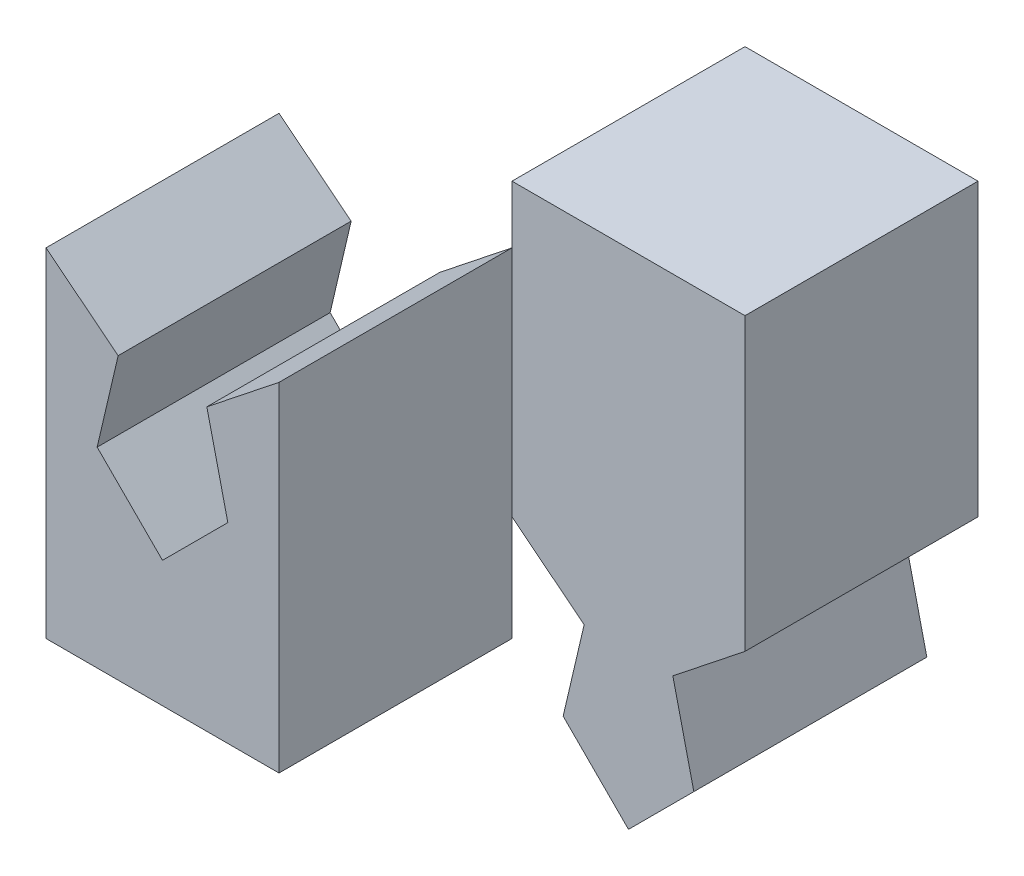
SolidWorks part; units mm, degrees
ref_plane "Front Plane" through (0, 0, 0) normal (0, 0, 1) x (1, 0, 0)
ref_plane "Top Plane" through (0, 0, 0) normal (0, 1, 0) x (1, 0, 0)
ref_plane "Right Plane" through (0, 0, 0) normal (1, 0, 0) x (0, 0, -1)
sketch "Sketch2" plane through (0, 0, 0) normal (0, 1, 0) x (1, 0, 0)
  line L1 (-2.5, 2.5) -> (2.5, 2.5)
  line L2 (-2.5, 2.5) -> (-2.5, -2.5)
  line L3 (-2.5, -2.5) -> (2.5, -2.5)
  line L4 (2.5, 2.5) -> (2.5, -2.5)
  line L5 (-2.5, 2.5) -> (2.5, -2.5) construction
  line L6 (-2.5, -2.5) -> (2.5, 2.5) construction
  point P0 (0, 0)
  dimension "D1" = 5
  dimension "D2" = 5
extrude "Boss-Extrude1" add sketch "Sketch2" along normal blind 13.5 contours L2 L1 L4 L3
sketch "Sketch4" plane through (0, 0, 0) normal (0, 1, 0) x (1, 0, 0)
  line L0 (-2.5, 2.5) -> (2.5, 2.5) construction
  line L1 (7.5, 2.5) -> (12.5, 2.5)
  line L2 (7.5, 2.5) -> (7.5, -2.5)
  line L3 (7.5, -2.5) -> (12.5, -2.5)
  line L4 (12.5, 2.5) -> (12.5, -2.5)
  line L5 (7.5, 2.5) -> (12.5, -2.5) construction
  line L6 (7.5, -2.5) -> (12.5, 2.5) construction
  line L7 (-2.5, 2.5) -> (-2.5, -2.5) construction
  point P0 (10, 0)
  point P10 (0, 0)
  dimension "D1" = 10
extrude "Boss-Extrude2" add sketch "Sketch4" along normal blind 13.5 separate body
ref_plane "Plane5" through (0, 0, 2.5) normal (0, 0, 1) x (1, 0, 0)
sketch "Sketch5" plane through (0, 0, 2.5) normal (0, 0, 1) x (1, 0, 0)
  line L9 (0, 0) -> (0, 12.9028) construction
  line L10 (-2.5, 7.2609) -> (-0.9515, 6.0314)
  line L11 (-2.5, 13.5) -> (-2.5, 0) construction
  line L12 (-0.9515, 6.0314) -> (-1.4023, 4.1053)
  line L13 (-1.4023, 4.1053) -> (0, 2.703)
  line L14 (0.9515, 6.0314) -> (1.4023, 4.1053)
  line L15 (2.5, 7.2609) -> (0.9515, 6.0314)
  line L16 (1.4023, 4.1053) -> (0, 2.703)
  line L17 (5, 0) -> (5, 13.2669) construction
  line L18 (2.75, 0) -> (-2.75, 0) construction
  line L19 (7.5, 7.2609) -> (9.0485, 6.0314)
  line L20 (9.0485, 6.0314) -> (8.5977, 4.1053)
  line L21 (8.5977, 4.1053) -> (10, 2.703)
  line L22 (11.4023, 4.1053) -> (10, 2.703)
  line L23 (10.9515, 6.0314) -> (11.4023, 4.1053)
  line L24 (12.5, 7.2609) -> (10.9515, 6.0314)
  line L25 (-2.5, 7.2609) -> (-2.5, 13.5)
  line L26 (-2.5, 13.5) -> (2.5, 13.5)
  line L27 (2.5, 13.5) -> (2.5, 7.2609)
  line L28 (7.5, 7.2609) -> (7.5, 0)
  line L29 (7.5, 13.5) -> (7.5, 0) construction
  line L30 (7.5, 0) -> (12.5, 0)
  line L31 (12.5, 0) -> (12.5, 7.2609)
  point P31 (-1.7381, 5.002)
  point P32 (-1.3216, 6.6157)
  point P33 (-1.4951, 4.7765)
  point P34 (-2.5, 6.9801)
  point P35 (-0.6102, 6.286)
  point P36 (-2.5, 7.0322)
  point P37 (-1.9289, 4.2039)
  point P38 (-1.1828, 5.8349)
  point P39 (-1.4604, 4.0477)
  point P40 (-0.9225, 5.8696)
  point P41 (-2.5, 7.2609)
  point P42 (-1.4023, 4.1053)
  point P43 (-0.9515, 6.0314)
  dimension "D1" = 5
extrude "Cut-Extrude1" cut sketch "Sketch5" against normal blind 13.5
equation "\"PCBDist\"= 13.5"
equation "\"D1@Boss-Extrude1\"=\"PCBDist\""
equation "\"D1@Boss-Extrude2\"=\"PCBDist\""
equation "\"BodyDist\"= 10"
equation "\"D1@Sketch4\"=\"BodyDist\""
equation "\"D1@Sketch5\"=\"BodyDist\"/2"
